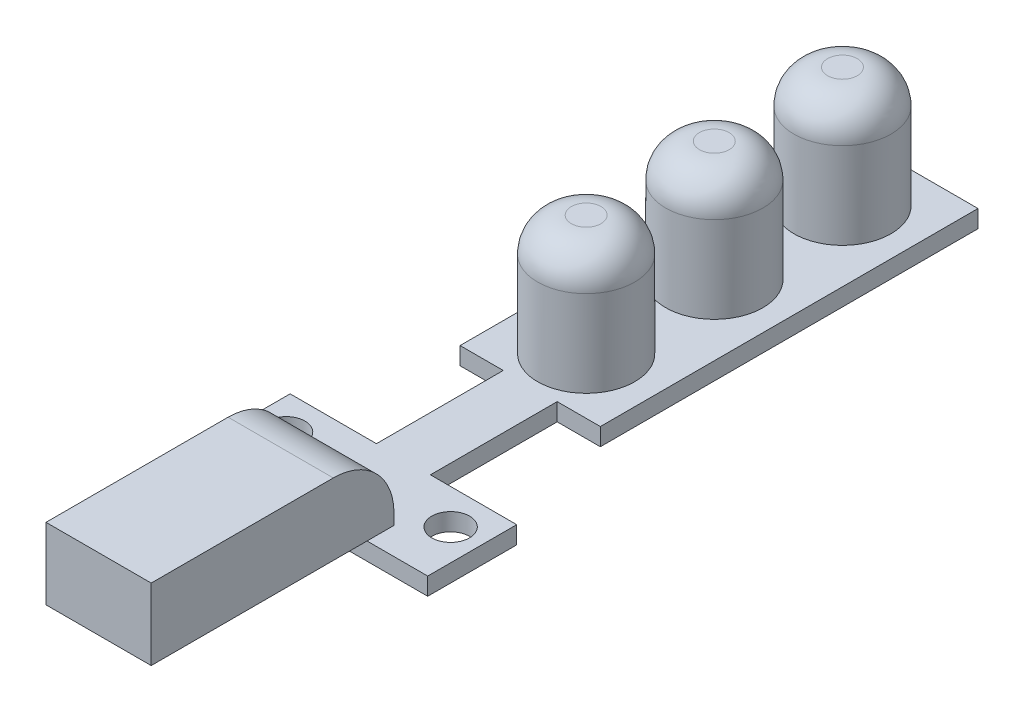
SolidWorks part; units mm, degrees
ref_plane "Front Plane" through (0, 0, 0) normal (0, 0, 1) x (1, 0, 0)
ref_plane "Top Plane" through (0, 0, 0) normal (0, 1, 0) x (1, 0, 0)
ref_plane "Right Plane" through (0, 0, 0) normal (1, 0, 0) x (0, 0, -1)
sketch "Sketch1" plane through (0, 0, 0) normal (0, 1, 0) x (1, 0, 0)
  line L0 (0, -29.718) -> (0, -38.1) construction
  line L1 (-6.604, -17.78) -> (6.604, -17.78)
  line L2 (-6.604, -17.78) -> (-6.604, 17.78)
  line L3 (-6.604, 17.78) -> (6.604, 17.78)
  line L4 (6.604, -17.78) -> (6.604, 17.78)
  line L5 (-6.604, -17.78) -> (6.604, 17.78) construction
  line L6 (-6.604, 17.78) -> (6.604, -17.78) construction
  line L7 (-2.54, -17.78) -> (2.54, -17.78)
  line L8 (-2.54, -17.78) -> (-2.54, -29.718)
  line L9 (-2.54, -29.718) -> (2.54, -29.718)
  line L10 (2.54, -17.78) -> (2.54, -29.718)
  line L11 (10.668, -29.718) -> (-10.668, -29.718)
  line L12 (10.668, -29.718) -> (10.668, -38.1)
  line L13 (10.668, -38.1) -> (-10.668, -38.1)
  line L14 (-10.668, -29.718) -> (-10.668, -38.1)
  circle A0 centre (-7.747, -33.02) radius 1.778
  circle A1 centre (7.747, -33.02) radius 1.778
  point P0 (0, 0)
  point P10 (0, -29.718)
  point P15 (0, -38.1)
  point P22 (0, 0)
  point P23 (0, 0)
  dimension "D7" = 3.556
  dimension "D1" = 13.208
  dimension "D2" = 35.56
  dimension "D3" = 11.938
  dimension "D4" = 5.08
  dimension "D5" = 21.336
  dimension "D6" = 8.382
  dimension "D8" = 2.921
  dimension "D9" = 3.302
extrude "Boss-Extrude1" add sketch "Sketch1" along normal blind 1.651 contours L11 L14 L13 L12 L9 A0 A1 | L10 L1 L8 L9
sketch "Sketch2" plane through (0, 1.651, 0) normal (0, 1, 0) x (1, 0, 0)
  line L0 (-6.604, 17.78) -> (6.604, 17.78) construction
  circle A0 centre (0, 11.6205) radius 4.572
  circle A1 centre (0, -0.4445) radius 4.572
  circle A2 centre (0, -12.5095) radius 4.572
  point P6 (0, 0)
  point P7 (0, -2.7058)
  dimension "D1" = 9.144
  dimension "D2" = 9.144
  dimension "D3" = 9.144
  dimension "D6" = 6.1595
  dimension "D4" = 12.065
  dimension "D5" = 12.065
extrude "Boss-Extrude2" add sketch "Sketch2" along normal blind 11.303
fillet "Fillet1" radius 3.175 3 edges at (0, 12.954, -7.0485) (0, 12.954, 5.0165) (0, 12.954, 17.0815)
sketch "Sketch3" plane through (0, 1.651, 0) normal (0, 1, 0) x (1, 0, 0)
  line L0 (10.668, -38.1) -> (-10.668, -38.1) construction
  line L1 (4.953, -35.56) -> (-4.953, -35.56)
  line L2 (4.953, -35.56) -> (4.953, -58.42)
  line L3 (4.953, -58.42) -> (-4.953, -58.42)
  line L4 (-4.953, -35.56) -> (-4.953, -58.42)
  line L5 (-6.604, 17.78) -> (6.604, 17.78) construction
  line L6 (-6.604, 17.78) -> (6.604, 17.78)
  point P5 (0, 17.78)
  point P6 (0, -35.56)
  line M18 (-10.668, -38.1) -> (10.668, -38.1)
  dimension "D1" = 9.906
  dimension "D2" = 2.54
  dimension "D3" = 22.86
extrude "Boss-Extrude3" add sketch "Sketch3" along normal blind 6.731 contours L1 L4 L2 M18 | L4 L3 L2 M18
fillet "Fillet2" radius 5.715 1 edges at (0, 8.382, 35.56)
